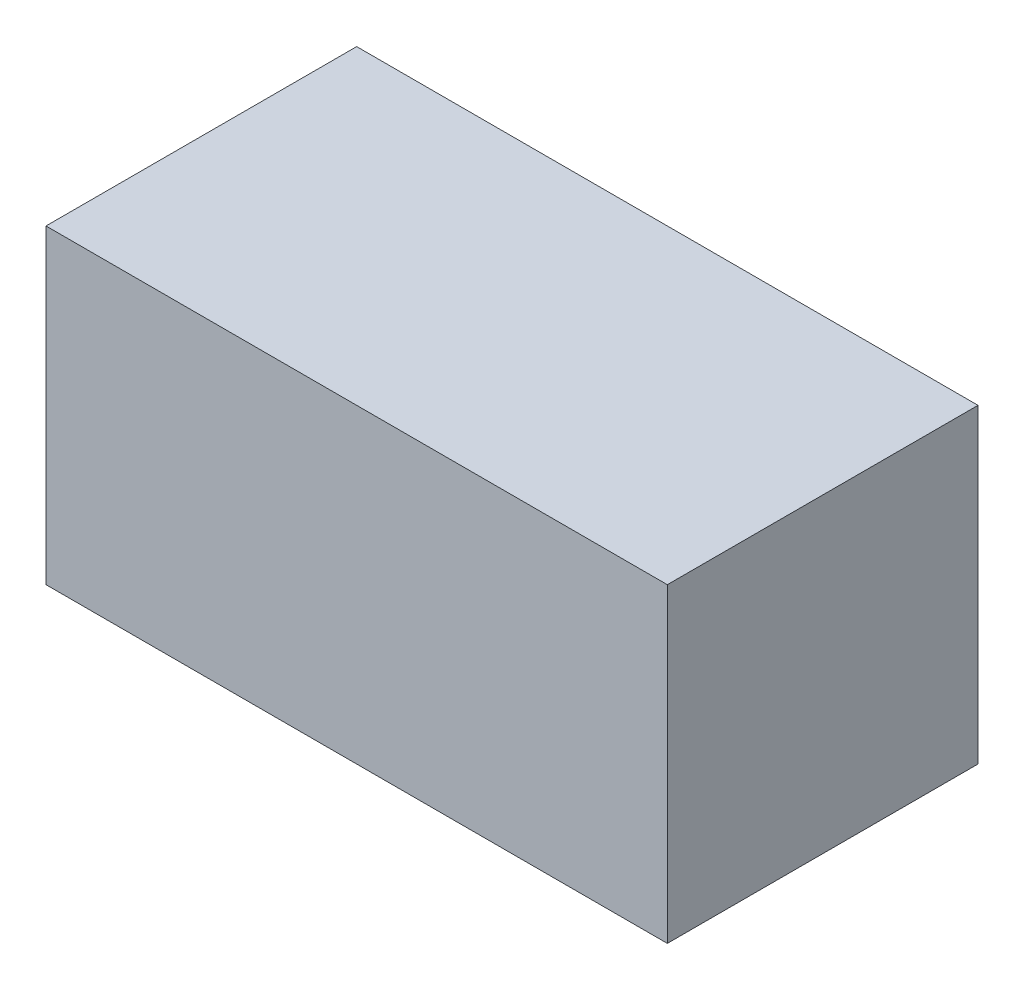
SolidWorks part; units mm, degrees
ref_plane "Front Plane" through (0, 0, 0) normal (0, 0, 1) x (1, 0, 0)
ref_plane "Top Plane" through (0, 0, 0) normal (0, 1, 0) x (1, 0, 0)
ref_plane "Right Plane" through (0, 0, 0) normal (1, 0, 0) x (0, 0, -1)
sketch "Sketch1" plane through (0, 0, 0) normal (0, 0, 1) x (1, 0, 0)
  line L1 (0, 0) -> (20, 0)
  line L2 (0, 0) -> (0, 10)
  line L3 (0, 10) -> (20, 10)
  line L4 (20, 0) -> (20, 10)
  dimension "D1" = 10
  dimension "D2" = 20
extrude "Boss-Extrude1" add sketch "Sketch1" against normal blind 10
